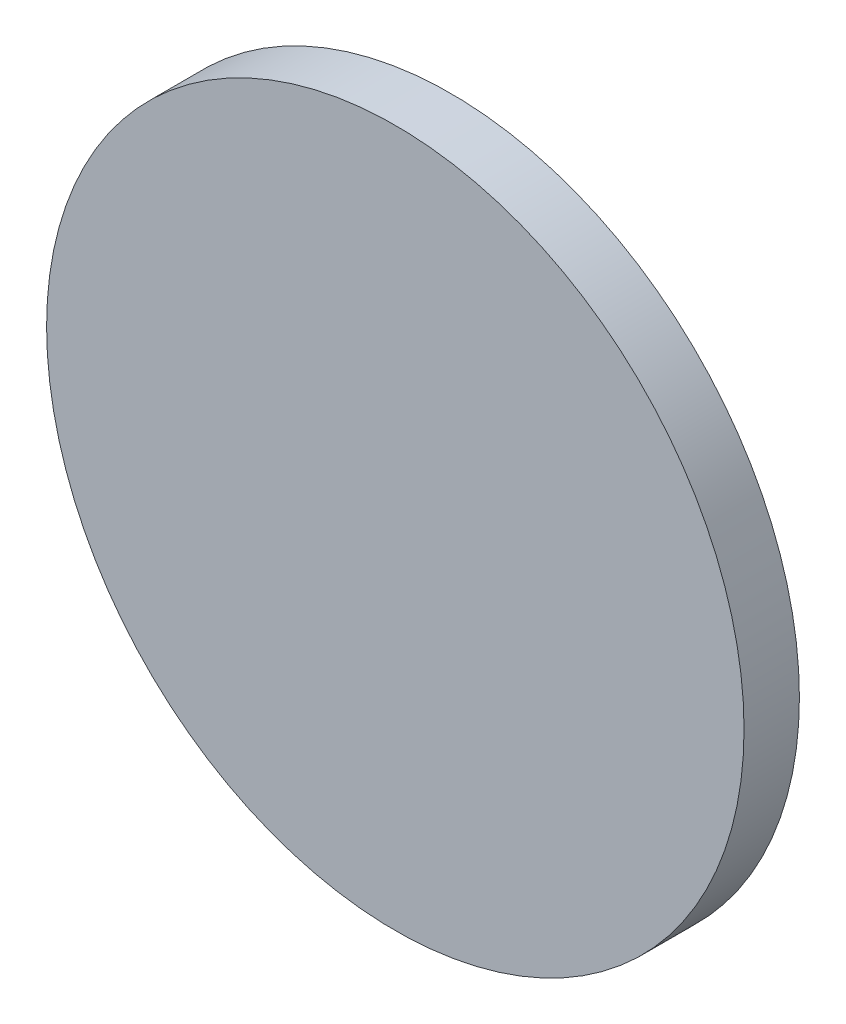
SolidWorks part; units mm, degrees
material "Plástico personalizado (1)"
ref_plane "Plano frontal" through (0, 0, 0) normal (0, 0, 1) x (1, 0, 0)
ref_plane "Plano superior" through (0, 0, 0) normal (0, 1, 0) x (1, 0, 0)
ref_plane "Plano direito" through (0, 0, 0) normal (1, 0, 0) x (0, 0, -1)
sketch "Esboço1" plane through (0, 0, 0) normal (0, 0, 1) x (1, 0, 0)
  circle A0 centre (0, 0) radius 31.5
extrude "Ressalto-extrusão1" add sketch "Esboço1" along normal blind 5
